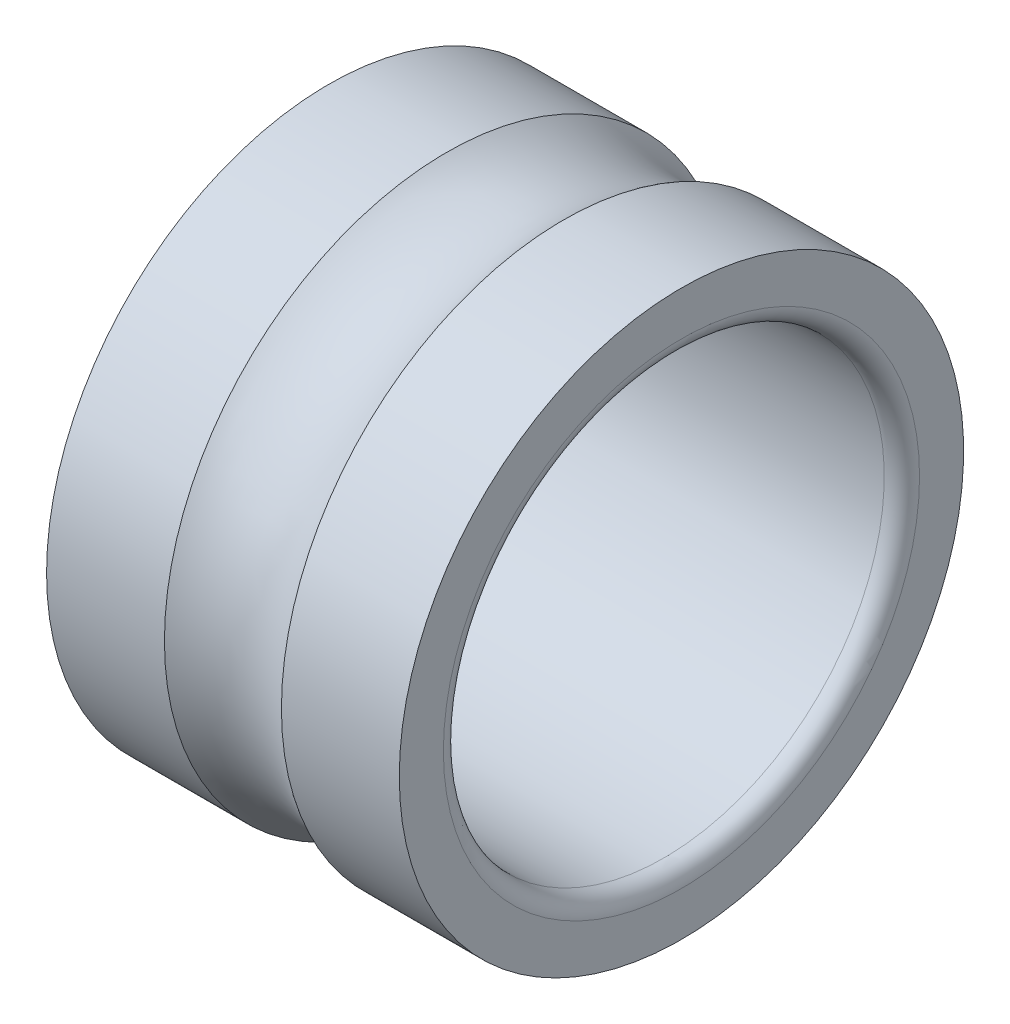
SolidWorks part; units mm, degrees
ref_plane "Front Plane" through (0, 0, 0) normal (0, 0, 1) x (1, 0, 0)
ref_plane "Top Plane" through (0, 0, 0) normal (0, 1, 0) x (1, 0, 0)
ref_plane "Right Plane" through (0, 0, 0) normal (1, 0, 0) x (0, 0, -1)
sketch "Sketch1" plane through (0, 0, 0) normal (0, 0, 1) x (1, 0, 0)
  line L0 (-27.7778, 0) -> (34.3333, 0) construction
  line L1 (0, 0) -> (0, 14.25) construction
  line L2 (10, 16) -> (3.3166, 16)
  line L3 (10, 16) -> (10, 13.5)
  line L4 (9, 12.5) -> (-9, 12.5)
  line L5 (-10, 16) -> (-10, 13.5)
  line L6 (10, 16) -> (-10, 12.5) construction
  line L7 (10, 12.5) -> (-10, 16) construction
  line L8 (-3.3166, 16) -> (-10, 16)
  arc A0 (-3.3166, 16) -> (3.3166, 16) centre (0, 21) ccw
  arc A1 (10, 13.5) -> (9, 12.5) centre (9, 13.5) cw
  arc A2 (-9, 12.5) -> (-10, 13.5) centre (-9, 13.5) cw
  point P3 (0, 14.25)
  dimension "D5" = 6
  dimension "D6" = 1
  dimension "D1" = 20
  dimension "D2" = 32
  dimension "D3" = 25
  dimension "D4" = 5
revolve "Revolve1" add sketch "Sketch1" angle 360 about L0
